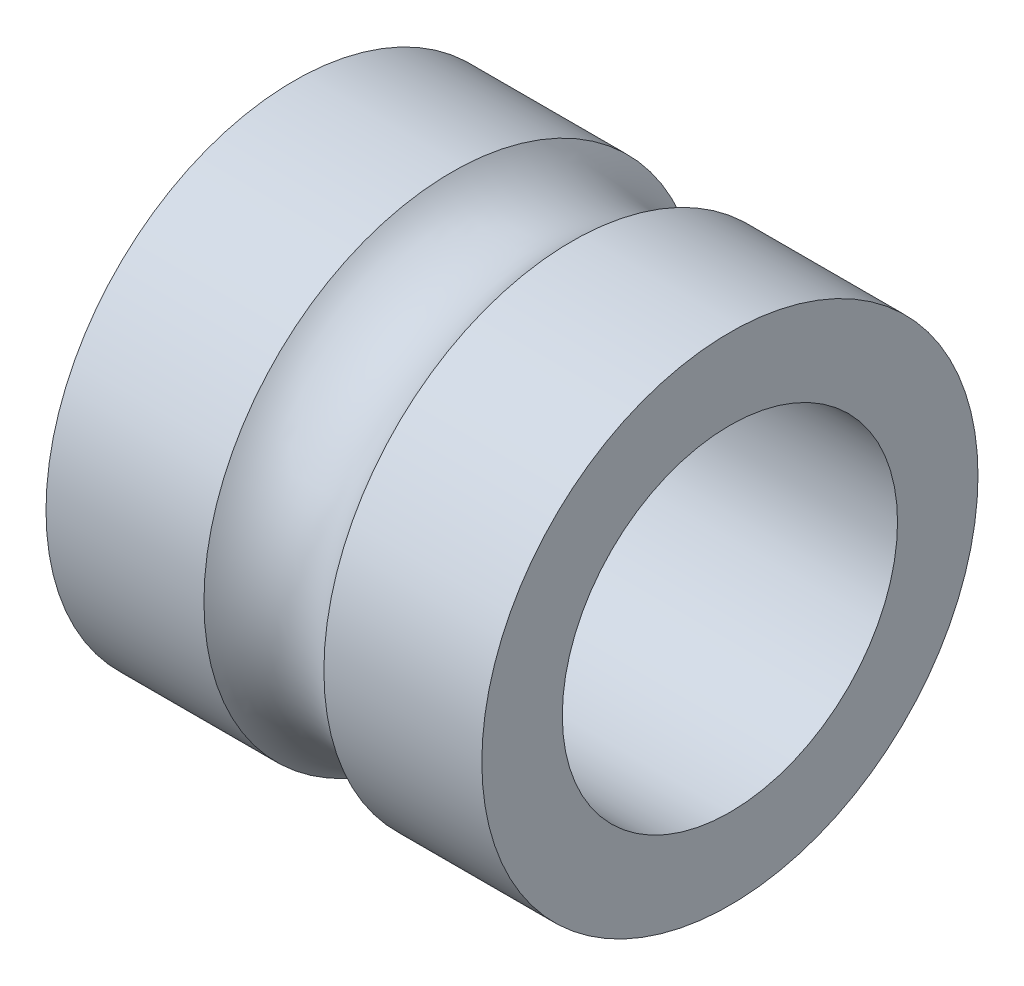
SolidWorks part; units mm, degrees
ref_plane "Front Plane" through (0, 0, 0) normal (0, 0, 1) x (1, 0, 0)
ref_plane "Top Plane" through (0, 0, 0) normal (0, 1, 0) x (1, 0, 0)
ref_plane "Right Plane" through (0, 0, 0) normal (1, 0, 0) x (0, 0, -1)
sketch "Sketch1" plane through (0, 0, 0) normal (0, 0, 1) x (1, 0, 0)
  line L0 (0, 0) -> (22479.1246, 0) construction
  line L1 (2.7521, 11.3846) -> (10, 11.3846)
  line L2 (-10, 11.3846) -> (-2.7521, 11.3846)
  line L3 (-10, 11.3846) -> (-10, 7.6923)
  line L4 (-10, 7.6923) -> (10, 7.6923)
  line L5 (10, 11.3846) -> (10, 7.6923)
  line L6 (-10, 11.3846) -> (10, 7.6923) construction
  line L7 (-10, 7.6923) -> (10, 11.3846) construction
  arc A0 (-2.7521, 11.3846) -> (2.7521, 11.3846) centre (0, 13.8462) ccw
  point P3 (0, 9.5385)
  dimension "D4" = 7.3846
  dimension "D5" = 2.4615
  dimension "D1" = 20
  dimension "D2" = 7.6923
  dimension "D3" = 11.3846
revolve "Revolve1" add sketch "Sketch1" angle 360 about L0
